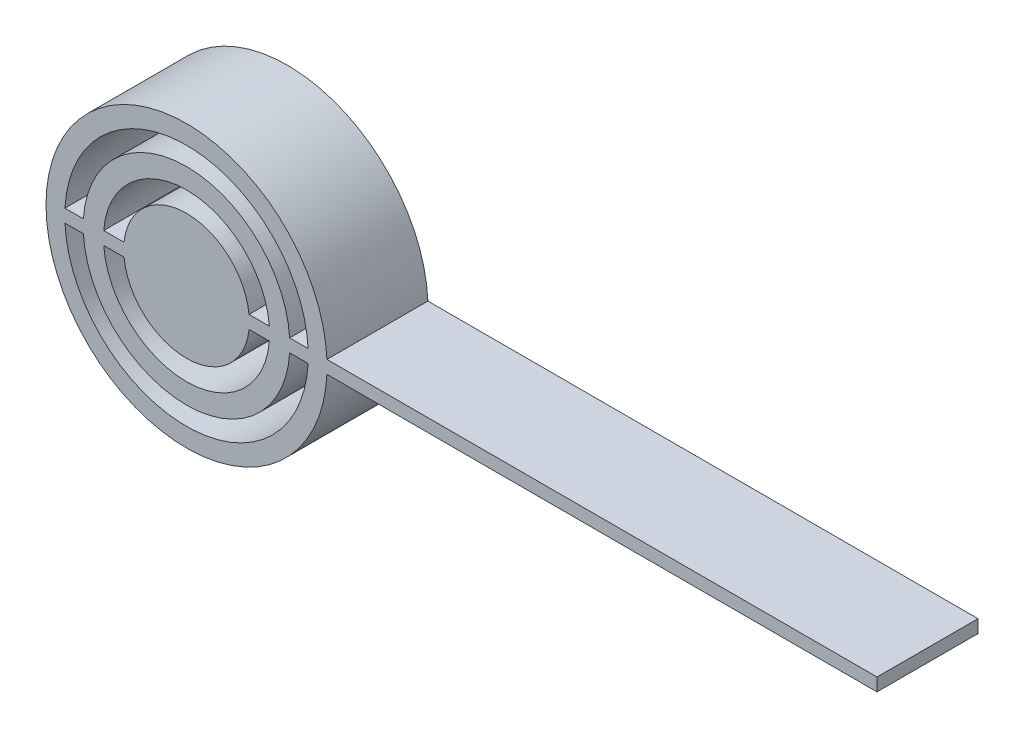
SolidWorks part; units mm, degrees
ref_plane "前视基准面" through (0, 0, 0) normal (0, 0, 1) x (1, 0, 0)
ref_plane "上视基准面" through (0, 0, 0) normal (0, 1, 0) x (1, 0, 0)
ref_plane "右视基准面" through (0, 0, 0) normal (1, 0, 0) x (0, 0, -1)
other "Configuration Table"
sketch "草图2" plane through (0, 0, 0) normal (0, 0, 1) x (1, 0, 0)
  line L0 (-48.1587, 2.5599) -> (-40.8456, 2.5599)
  line L1 (-55.6601, 2.5599) -> (-55.6012, 2.5599)
  line L2 (-55.6601, -2.5599) -> (-55.6012, -2.5599)
  line L3 (273.4865, -2.5599) -> (273.4865, 2.5599)
  line L4 (-48.1587, -2.5599) -> (-40.8456, -2.5599)
  line L5 (-32.7996, 2.5599) -> (-24.759, 2.5599)
  line L6 (-32.7996, -2.5599) -> (-24.759, -2.5599)
  line L7 (24.759, 2.5599) -> (32.7996, 2.5599)
  line L8 (24.759, -2.5599) -> (32.7996, -2.5599)
  line L9 (40.8456, 2.5599) -> (48.1587, 2.5599)
  line L10 (40.8456, -2.5599) -> (48.1587, -2.5599)
  line L11 (55.6012, 2.5599) -> (273.4865, 2.5599)
  line L12 (55.6012, -2.5599) -> (273.4865, -2.5599)
  arc A0 (55.6012, 2.5599) -> (55.6012, -2.5599) centre (0, 0) ccw
  arc A1 (-48.1587, -2.5599) -> (48.1587, -2.5599) centre (0, 0) ccw
  arc A2 (-40.8456, -2.5599) -> (40.8456, -2.5599) centre (0, 0) ccw
  arc A3 (-32.7996, -2.5599) -> (32.7996, -2.5599) centre (0, 0) ccw
  arc A4 (24.759, 2.5599) -> (-24.759, 2.5599) centre (0, 0) ccw
  arc A5 (48.1587, 2.5599) -> (-48.1587, 2.5599) centre (0, 0) ccw
  arc A6 (40.8456, 2.5599) -> (-40.8456, 2.5599) centre (0, 0) ccw
  arc A7 (32.7996, 2.5599) -> (-32.7996, 2.5599) centre (0, 0) ccw
  arc A8 (-24.759, -2.5599) -> (24.759, -2.5599) centre (0, 0) ccw
extrude "凸台-拉伸4" add sketch "草图2" along normal blind 40 contours L11 A0 L12 L3 A7 L7 A4 L5 L4 A2 L10 A1 L9 A6 L0 A5 L6 A8 L8 A3
